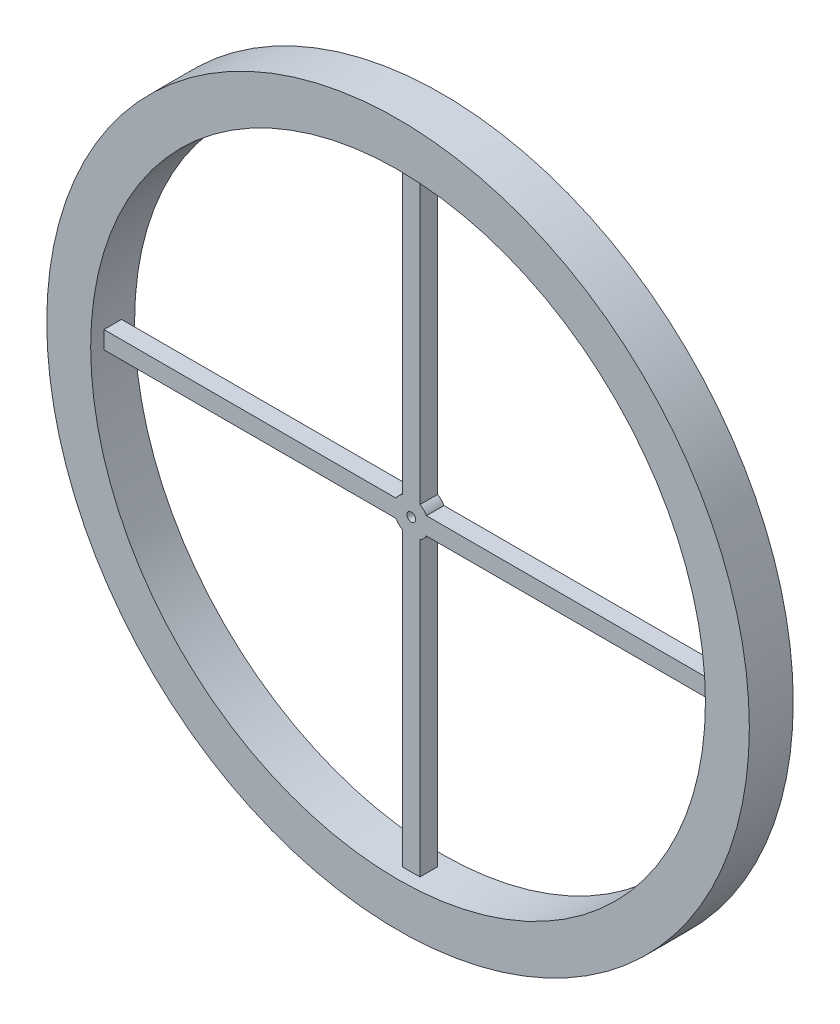
SolidWorks part; units mm, degrees
ref_plane "Front Plane" through (0, 0, 0) normal (0, 0, 1) x (1, 0, 0)
ref_plane "Top Plane" through (0, 0, 0) normal (0, 1, 0) x (1, 0, 0)
ref_plane "Right Plane" through (0, 0, 0) normal (1, 0, 0) x (0, 0, -1)
sketch "Sketch1" plane through (0, 0, 0) normal (0, 0, 1) x (1, 0, 0)
  line L0 (0, 40) -> (0, 0.5)
  line L2 (-1, 34.9857) -> (-1, 1.7321)
  line L4 (-1.7321, 1) -> (-34.9857, 1)
  line L5 (-1, 45.4801) -> (-1, -49.5397) construction
  line L6 (0, 45.4801) -> (0, -49.5397) construction
  line L10 (-0.5, 0) -> (-40, 0)
  arc A0 (-1, 34.9857) -> (-34.9857, 1) centre (0, 0) ccw
  arc A1 (0, 40) -> (-40, 0) centre (0, 0) ccw
  arc A6 (0, 0.5) -> (-0.5, 0) centre (0, 0) ccw
  arc A7 (-1, 1.7321) -> (-1.7321, 1) centre (0, 0) ccw
  circle A8 centre (0, 0) radius 0.5 construction
  circle A9 centre (0, 0) radius 2 construction
  circle A10 centre (0, 0) radius 35 construction
  circle A11 centre (0, 0) radius 40 construction
  point P6 (46.1702, 0)
  point P7 (-47.5217, 0)
  point P12 (46.1702, 1)
  point P13 (-47.5217, 1)
  dimension "D2" = 1
  dimension "D6" = 1
  dimension "D1" = 1
extrude "Boss-Extrude1" add sketch "Sketch1" along normal mid plane 2
pattern_circular "CirPattern1" count 4 every 90 about axis through (0, 0, 0) along (0, 0, 1) of "Boss-Extrude1"
sketch "Sketch3" plane through (0, 0, 0) normal (0, 0, 1) x (1, 0, 0)
  circle A0 centre (0, 0) radius 35
  circle A1 centre (0, 0) radius 40
extrude "Boss-Extrude2" add sketch "Sketch3" along normal mid plane 5
